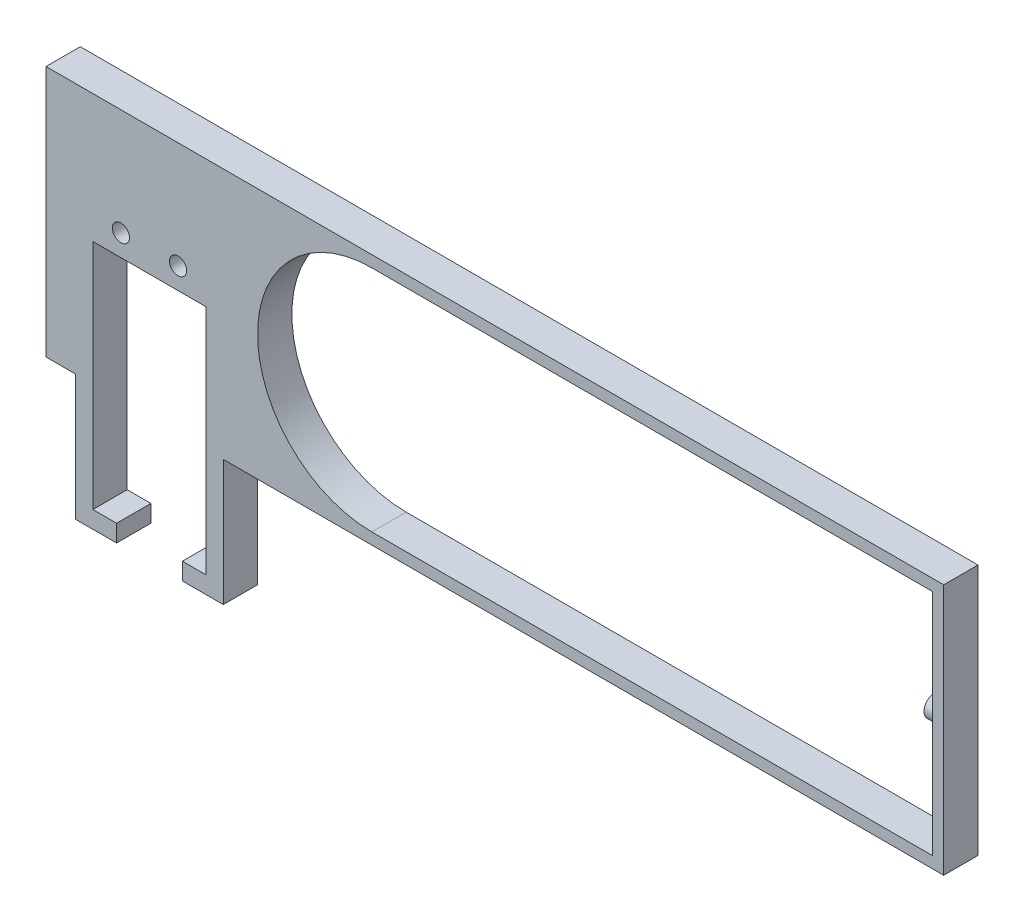
SolidWorks part; units mm, degrees
other "Markup1"
sketch "Sketch3" plane through (63.5, 44, 6) normal (0.035, 0.053, 0.998) x (0.9992, 0.0181, -0.036)
sketch "Sketch4" plane through (100, 44, 6) normal (0.035, 0.053, 0.998) x (0.9992, 0.0181, -0.036)
material "ABS"
ref_plane "Front Plane" through (0, 0, 0) normal (0, 0, 1) x (1, 0, 0)
ref_plane "Top Plane" through (0, 0, 0) normal (0, 1, 0) x (1, 0, 0)
ref_plane "Right Plane" through (0, 0, 0) normal (1, 0, 0) x (0, 0, -1)
sketch "Sketch1" plane through (0, 0, 0) normal (0, 0, 1) x (1, 0, 0)
  line L3 (0, 0) -> (100, 0)
  line L4 (100, 0) -> (100, 44)
  line L5 (100, 44) -> (0, 44)
  line L6 (0, 44) -> (-57, 44)
  line L7 (-57, 44) -> (-57, 0)
  line L8 (-57, 0) -> (-51.8, 0)
  line L9 (-51.8, 0) -> (-51.8, -22)
  line L10 (-51.8, -22) -> (-44.65, -22)
  line L11 (-44.65, -22) -> (-44.65, -19)
  line L12 (-44.65, -19) -> (-48.8, -19)
  line L13 (-48.8, -19) -> (-48.8, 21.6)
  line L14 (-48.8, 21.6) -> (-29, 21.6)
  line L15 (-29, 21.6) -> (-29, -19)
  line L16 (-29, -19) -> (-33.15, -19)
  line L17 (-33.15, -19) -> (-33.15, -22)
  line L18 (-33.15, -22) -> (-26, -22)
  line L20 (0, 2) -> (98, 2)
  line L21 (98, 2) -> (98, 42)
  line L22 (98, 42) -> (0, 42)
  line L23 (-43.9, 25.353) -> (-33.9, 25.353) construction
  line L24 (0, 0) -> (-26, 0)
  line L25 (-26, 0) -> (-26, -22)
  line L26 (-44.65, -19) -> (-33.15, -19) construction
  circle A1 centre (-43.9, 25.353) radius 1.5
  circle A2 centre (-33.9, 25.353) radius 1.5
  arc A3 (0, 42) -> (0, 2) centre (0, 22) ccw
  point P2 (-38.9, -19)
  point P28 (-38.9, 25.353)
  point P29 (-38.9, 21.6)
  point P30 (-20, 22)
  dimension "D1" = 2
  dimension "D5" = 20
  dimension "D7" = 3
  dimension "D8" = 3
  dimension "D2" = 2
  dimension "D3" = 2
  dimension "D4" = 120
  dimension "D6" = 3.753
  dimension "D9" = 10
  dimension "D10" = 8.2
  dimension "D11" = 40.6
  dimension "D12" = 19.8
  dimension "D13" = 11.5
  dimension "D14" = 3
  dimension "D15" = 3
  dimension "D16" = 3
  dimension "D17" = 22
  dimension "D18" = 37
extrude "Boss-Extrude1" add sketch "Sketch1" along normal blind 6
sketch "Sketch2" plane through (98, 0, 0) normal (-1, 0, 0) x (0, 0, 1)
  line L0 (3, 42) -> (3, 2) construction
  line L1 (6, 42) -> (0, 42) construction
  line L2 (6, 2) -> (0, 2) construction
  circle A0 centre (3, 22) radius 1.905
  point P2 (3, 22)
  dimension "D1" = 3.81
extrude "Boss-Extrude2" add sketch "Sketch2" along normal blind 2.54
